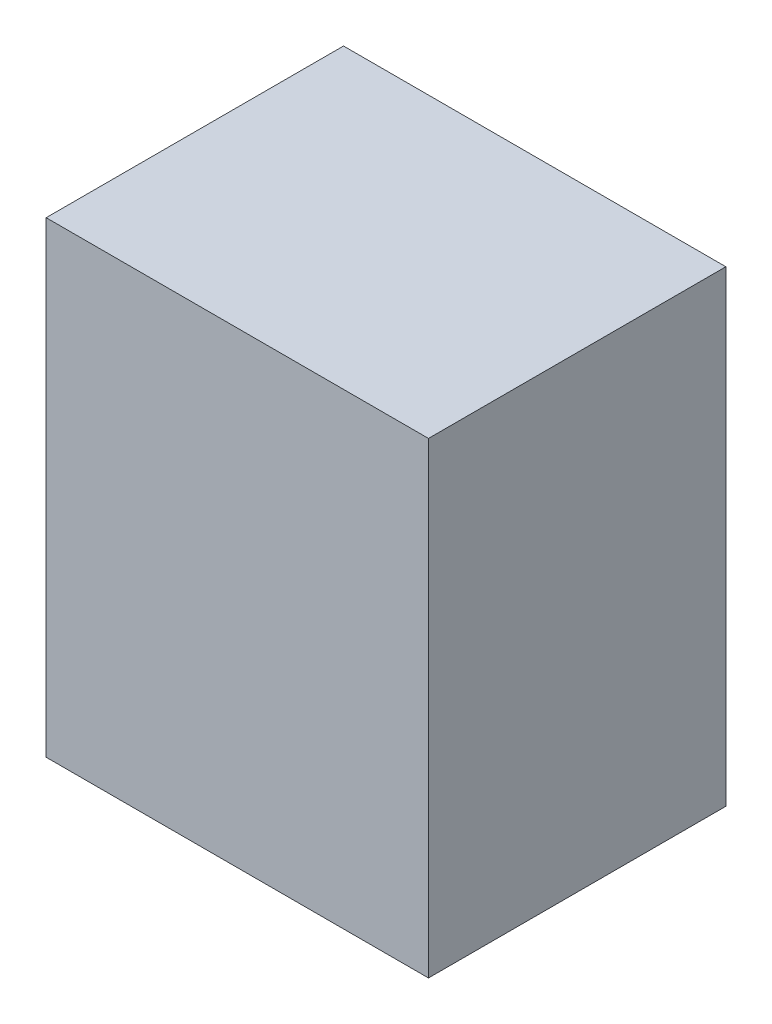
SolidWorks part; units mm, degrees
ref_plane "Front Plane" through (0, 0, 0) normal (0, 0, 1) x (1, 0, 0)
ref_plane "Top Plane" through (0, 0, 0) normal (0, 1, 0) x (1, 0, 0)
ref_plane "Right Plane" through (0, 0, 0) normal (1, 0, 0) x (0, 0, -1)
sketch "Sketch1" plane through (0, 0, 0) normal (0, 0, 1) x (1, 0, 0)
  line L1 (0, 0) -> (4.5, 0)
  line L2 (0, 0) -> (0, 5.5)
  line L3 (0, 5.5) -> (4.5, 5.5)
  line L4 (4.5, 0) -> (4.5, 5.5)
  dimension "D1" = 4.5
  dimension "D2" = 5.5
extrude "Boss-Extrude1" add sketch "Sketch1" along normal blind 3.5
